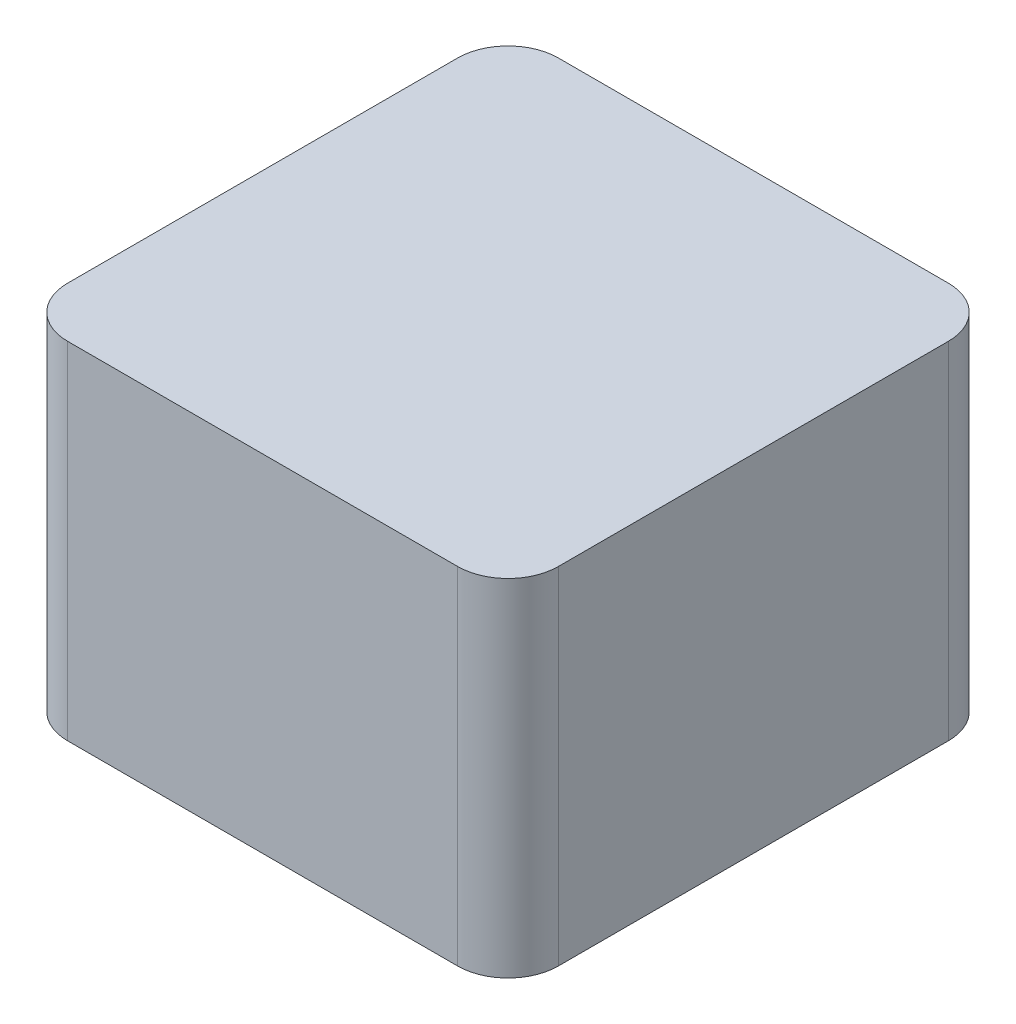
SolidWorks part; units mm, degrees
ref_plane "Front Plane" through (0, 0, 0) normal (0, 0, 1) x (1, 0, 0)
ref_plane "Top Plane" through (0, 0, 0) normal (0, 1, 0) x (1, 0, 0)
ref_plane "Right Plane" through (0, 0, 0) normal (1, 0, 0) x (0, 0, -1)
sketch "Sketch1" plane through (0, 123.7242, 0) normal (0, -1, 0) x (1, 0, 0)
  line L0 (88.9764, 216.9461) -> (88.9764, 210.7461) construction
  line L1 (80.7764, 210.7461) -> (80.7764, 216.9461) construction
  line L2 (81.7764, 217.9461) -> (87.9764, 217.9461) construction
  line L3 (87.9764, 209.7461) -> (81.7764, 209.7461) construction
  line L4 (80.7764, 210.7461) -> (80.7764, 216.9461) construction
  line L5 (81.7764, 217.9461) -> (87.9764, 217.9461) construction
  line L6 (88.9764, 216.9461) -> (88.9764, 210.7461) construction
  line L7 (87.9764, 209.7461) -> (81.7764, 209.7461) construction
  line L8 (80.9764, 210.7461) -> (80.9764, 216.9461)
  line L9 (81.7764, 217.7461) -> (87.9764, 217.7461)
  line L10 (88.7764, 216.9461) -> (88.7764, 210.7461)
  line L11 (87.9764, 209.9461) -> (81.7764, 209.9461)
  arc A0 (80.7764, 210.7461) -> (81.7764, 209.7461) centre (81.7764, 210.7461) ccw construction
  arc A1 (81.7764, 217.9461) -> (80.7764, 216.9461) centre (81.7764, 216.9461) ccw construction
  arc A2 (88.9764, 216.9461) -> (87.9764, 217.9461) centre (87.9764, 216.9461) ccw construction
  arc A3 (87.9764, 209.7461) -> (88.9764, 210.7461) centre (87.9764, 210.7461) ccw construction
  arc A4 (80.7764, 210.7461) -> (81.7764, 209.7461) centre (81.7764, 210.7461) ccw construction
  arc A5 (81.7764, 217.9461) -> (80.7764, 216.9461) centre (81.7764, 216.9461) ccw construction
  arc A6 (88.9764, 216.9461) -> (87.9764, 217.9461) centre (87.9764, 216.9461) ccw construction
  arc A7 (87.9764, 209.7461) -> (88.9764, 210.7461) centre (87.9764, 210.7461) ccw construction
  arc A8 (81.7764, 217.7461) -> (80.9764, 216.9461) centre (81.7764, 216.9461) ccw
  arc A9 (88.7764, 216.9461) -> (87.9764, 217.7461) centre (87.9764, 216.9461) ccw
  arc A10 (87.9764, 209.9461) -> (88.7764, 210.7461) centre (87.9764, 210.7461) ccw
  arc A11 (80.9764, 210.7461) -> (81.7764, 209.9461) centre (81.7764, 210.7461) ccw
  dimension "D1" = 0.2
extrude "Boss-Extrude1" add sketch "Sketch1" against normal blind 5.5 from offset 1
